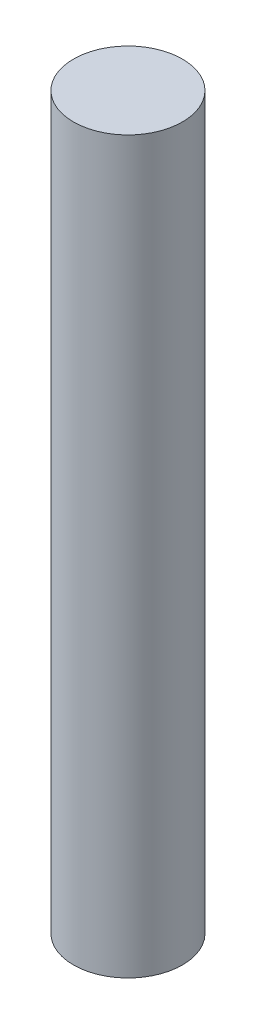
SolidWorks part; units mm, degrees
ref_plane "Front Plane" through (0, 0, 0) normal (0, 0, 1) x (1, 0, 0)
ref_plane "Top Plane" through (0, 0, 0) normal (0, 1, 0) x (1, 0, 0)
ref_plane "Right Plane" through (0, 0, 0) normal (1, 0, 0) x (0, 0, -1)
sketch "Sketch1" plane through (0, 0, 0) normal (0, 1, 0) x (1, 0, 0)
  circle A0 centre (0, 0) radius 3.175
  dimension "D1" = 6.35
extrude "Boss-Extrude1" add sketch "Sketch1" along normal blind 42.545
